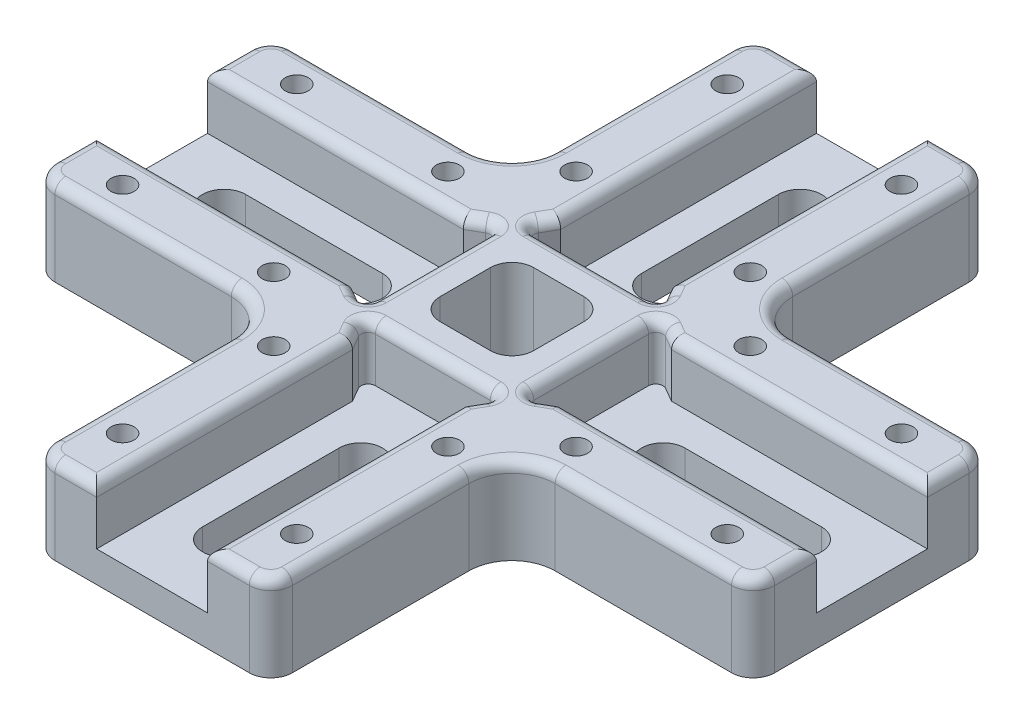
SolidWorks part; units mm, degrees
ref_plane "Front Plane" through (0, 0, 0) normal (0, 0, 1) x (1, 0, 0)
ref_plane "Top Plane" through (0, 0, 0) normal (0, 1, 0) x (1, 0, 0)
ref_plane "Right Plane" through (0, 0, 0) normal (1, 0, 0) x (0, 0, -1)
sketch "Sketch1" plane through (0, 0, 0) normal (0, 1, 0) x (1, 0, 0)
  line L0 (0, 54.7573) -> (0, -53.2039) construction
  line L1 (-56.4401, 0) -> (74.3042, 0) construction
  line L2 (0, 50) -> (-16.5, 50)
  line L3 (-16.5, 50) -> (-16.5, 16.5)
  line L4 (-16.5, 16.5) -> (-50, 16.5)
  line L5 (-50, 16.5) -> (-50, 0)
  line L6 (16.5, 50) -> (0, 50)
  line L7 (16.5, 16.5) -> (16.5, 50)
  line L8 (50, 16.5) -> (16.5, 16.5)
  line L9 (50, 0) -> (50, 16.5)
  line L10 (50, -16.5) -> (50, 0)
  line L11 (16.5, -16.5) -> (50, -16.5)
  line L12 (16.5, -50) -> (16.5, -16.5)
  line L13 (0, -50) -> (16.5, -50)
  line L14 (-16.5, -50) -> (0, -50)
  line L15 (-16.5, -16.5) -> (-16.5, -50)
  line L16 (-50, -16.5) -> (-16.5, -16.5)
  line L17 (-50, 0) -> (-50, -16.5)
  point P28 (0, 0)
  dimension "D1" = 50
  dimension "D2" = 50
  dimension "D3" = 16.5
  dimension "D4" = 16.5
  dimension "D5" = 4
extrude "Boss-Extrude1" add sketch "Sketch1" along normal blind 12
sketch "Sketch4" plane through (0, 12, 0) normal (0, 1, 0) x (1, 0, 0)
  line L0 (0, 50) -> (0, -50) construction
  line L1 (16.5, 50) -> (-16.5, 50) construction
  line L2 (-16.5, -50) -> (16.5, -50) construction
  line L3 (50, -7.7) -> (50, 7.7)
  line L4 (50, 7.7) -> (14.4641, 7.7)
  line L5 (14.4641, 7.7) -> (12.5, 8.834)
  line L6 (7.7, 50) -> (-7.7, 50)
  line L7 (-7.7, 50) -> (-7.7, 14.4641)
  line L8 (-7.7, 14.4641) -> (-8.834, 12.5)
  line L9 (-7.9679, 11) -> (7.9679, 11)
  line L10 (7.7, 14.4641) -> (8.834, 12.5)
  line L11 (7.7, 50) -> (7.7, 14.4641)
  line L14 (11, 7.9679) -> (11, -7.9679)
  line L15 (14.4641, -7.7) -> (12.5, -8.834)
  line L16 (50, -7.7) -> (14.4641, -7.7)
  line L17 (-7.7, -50) -> (7.7, -50)
  line L18 (7.7, -50) -> (7.7, -14.4641)
  line L19 (7.7, -14.4641) -> (8.834, -12.5)
  line L20 (7.9679, -11) -> (-7.9679, -11)
  line L21 (-7.7, -14.4641) -> (-8.834, -12.5)
  line L22 (-7.7, -50) -> (-7.7, -14.4641)
  line L23 (-50, 7.7) -> (-50, -7.7)
  line L24 (-50, -7.7) -> (-14.4641, -7.7)
  line L25 (-14.4641, -7.7) -> (-12.5, -8.834)
  line L26 (-11, -7.9679) -> (-11, 7.9679)
  line L27 (-14.4641, 7.7) -> (-12.5, 8.834)
  line L28 (-50, 7.7) -> (-14.4641, 7.7)
  arc A0 (-8.834, 12.5) -> (-7.9679, 11) centre (-7.9679, 12) ccw
  arc A1 (8.834, 12.5) -> (7.9679, 11) centre (7.9679, 12) cw
  arc A2 (12.5, 8.834) -> (11, 7.9679) centre (12, 7.9679) ccw
  arc A3 (12.5, -8.834) -> (11, -7.9679) centre (12, -7.9679) cw
  arc A4 (8.834, -12.5) -> (7.9679, -11) centre (7.9679, -12) ccw
  arc A5 (-8.834, -12.5) -> (-7.9679, -11) centre (-7.9679, -12) cw
  arc A6 (-12.5, -8.834) -> (-11, -7.9679) centre (-12, -7.9679) ccw
  arc A7 (-12.5, 8.834) -> (-11, 7.9679) centre (-12, 7.9679) cw
  point P6 (-4.9087, -5.1)
  point P18 (-9.7, 11)
  point P22 (0, 11)
  point P24 (9.7, 11)
  point P32 (11, 0)
  point P34 (11, -9.7)
  point P44 (0, -11)
  point P46 (-9.7, -11)
  point P56 (-11, 0)
  point P58 (-11, 9.7)
  point P59 (0, 0)
  dimension "D5" = 1
  dimension "D1" = 7.7
  dimension "D2" = 39
  dimension "D3" = 60
  dimension "D4" = 2
extrude "Cut-Extrude1" cut sketch "Sketch4" against normal blind 7.7
sketch "Sketch5" plane through (0, 12, 0) normal (0, 1, 0) x (1, 0, 0)
  line L0 (0, 0) -> (0, 61.5072) construction
  line L6 (-22.7133, 21) -> (27.3657, 21) construction
  line L7 (-24.8812, 42) -> (27.3657, 42) construction
  line L8 (-7.9679, 11) -> (7.9679, 11) construction
  line L9 (-7.7, 50) -> (-16.5, 50) construction
  line L10 (-12.1, 50) -> (-12.1, 12.9915) construction
  circle A0 centre (-12.1, 42) radius 1.6
  circle A1 centre (-12.1, 21) radius 1.6
  circle A2 centre (12.1, 21) radius 1.6
  circle A3 centre (12.1, 42) radius 1.6
  circle A4 centre (42, 12.1) radius 1.6
  circle A5 centre (21, 12.1) radius 1.6
  circle A6 centre (21, -12.1) radius 1.6
  circle A7 centre (42, -12.1) radius 1.6
  circle A8 centre (12.1, -42) radius 1.6
  circle A9 centre (12.1, -21) radius 1.6
  circle A10 centre (-12.1, -21) radius 1.6
  circle A11 centre (-12.1, -42) radius 1.6
  circle A12 centre (-42, -12.1) radius 1.6
  circle A13 centre (-21, -12.1) radius 1.6
  circle A14 centre (-21, 12.1) radius 1.6
  circle A15 centre (-42, 12.1) radius 1.6
  point P47 (0, 0)
  dimension "D3" = 3.2
  dimension "D4" = 3.2
  dimension "D1" = 10
  dimension "D2" = 8
extrude "Cut-Extrude2" cut sketch "Sketch5" against normal through all
sketch "Sketch7" plane through (0, 0, 0) normal (0, -1, 0) x (1, 0, 0)
  line L0 (0, 0) -> (0, 61.7218) construction
  circle A0 centre (-12.1, 42) radius 3.25
  circle A1 centre (-12.1, 21) radius 3.25
  circle A2 centre (12.1, 21) radius 3.25
  circle A3 centre (12.1, 42) radius 3.25
  circle A4 centre (42, 12.1) radius 3.25
  circle A5 centre (21, 12.1) radius 3.25
  circle A6 centre (21, -12.1) radius 3.25
  circle A7 centre (42, -12.1) radius 3.25
  circle A8 centre (12.1, -42) radius 3.25
  circle A9 centre (12.1, -21) radius 3.25
  circle A10 centre (-12.1, -21) radius 3.25
  circle A11 centre (-12.1, -42) radius 3.25
  circle A12 centre (-42, -12.1) radius 3.25
  circle A13 centre (-21, -12.1) radius 3.25
  circle A14 centre (-21, 12.1) radius 3.25
  circle A15 centre (-42, 12.1) radius 3.25
  point P39 (0, 0)
  dimension "D1" = 6.5
  dimension "D2" = 6.5
extrude "Cut-Extrude3" cut sketch "Sketch7" against normal blind 8.5
fillet "Fillet1" radius 6 4 edges at (-16.5, 6, -16.5) (16.5, 6, -16.5) (-16.5, 6, 16.5) (16.5, 6, 16.5)
fillet "Fillet3" radius 3 8 edges at (-50, 6, 16.5) (-50, 6, -16.5) (-16.5, 6, -50) (16.5, 6, -50) (50, 6, -16.5) (50, 6, 16.5) (16.5, 6, 50) (-16.5, 6, 50)
sketch "Sketch9" plane through (0, 12, 0) normal (0, 1, 0) x (1, 0, 0)
  line L0 (0, 0) -> (0, 50) construction
  line L1 (7.7, 50) -> (-7.7, 50) construction
  line L2 (0, 40) -> (0, 21) construction
  line L3 (3, 40) -> (3, 21)
  line L4 (-3, 40) -> (-3, 21)
  line L5 (-7.9679, 11) -> (7.9679, 11) construction
  line L6 (40, 0) -> (21, 0) construction
  line L7 (-3.5, 6.5) -> (3.5, 6.5)
  line L8 (-6.5, 3.5) -> (-6.5, -3.5)
  line L9 (-3.5, -6.5) -> (3.5, -6.5)
  line L10 (6.5, 3.5) -> (6.5, -3.5)
  line L11 (-6.5, 6.5) -> (6.5, -6.5) construction
  line L12 (-6.5, -6.5) -> (6.5, 6.5) construction
  line L13 (40, -3) -> (21, -3)
  line L14 (40, 3) -> (21, 3)
  line L15 (0, -40) -> (0, -21) construction
  line L16 (-3, -40) -> (-3, -21)
  line L17 (3, -40) -> (3, -21)
  line L18 (-40, 0) -> (-21, 0) construction
  line L19 (-40, 3) -> (-21, 3)
  line L20 (-40, -3) -> (-21, -3)
  arc A0 (3, 40) -> (-3, 40) centre (0, 40) ccw
  arc A1 (-3, 21) -> (3, 21) centre (0, 21) ccw
  arc A2 (3.5, 6.5) -> (6.5, 3.5) centre (3.5, 3.5) cw
  arc A3 (3.5, -6.5) -> (6.5, -3.5) centre (3.5, -3.5) ccw
  arc A4 (-6.5, -3.5) -> (-3.5, -6.5) centre (-3.5, -3.5) ccw
  arc A5 (-3.5, 6.5) -> (-6.5, 3.5) centre (-3.5, 3.5) ccw
  arc A6 (40, -3) -> (40, 3) centre (40, 0) ccw
  arc A7 (21, 3) -> (21, -3) centre (21, 0) ccw
  arc A8 (-3, -40) -> (3, -40) centre (0, -40) ccw
  arc A9 (3, -21) -> (-3, -21) centre (0, -21) ccw
  arc A10 (-40, 3) -> (-40, -3) centre (-40, 0) ccw
  arc A11 (-21, -3) -> (-21, 3) centre (-21, 0) ccw
  point P7 (0, 30.5)
  point P35 (30.5, 0)
  point P42 (0, -30.5)
  point P49 (-30.5, 0)
  point P54 (0, 0)
  dimension "D6" = 3
  dimension "D1" = 6
  dimension "D2" = 10
  dimension "D3" = 10
  dimension "D4" = 13
  dimension "D5" = 13
extrude "Cut-Extrude5" cut sketch "Sketch9" against normal through all
fillet "Fillet5" radius 1.5 56 edges at (-50, 12, -10.6) (-49.1213, 12, -15.6213) (-34.75, 12, -16.5) (-18.2574, 12, -18.2574) (-16.5, 12, -34.75) (-15.6213, 12, -49.1213) (8.267, 12, -13.4821) (8.834, 12, -11.5) (0, 12, -11) (-8.834, 12, -11.5) (10.6, 12, -50) (15.6213, 12, -49.1213) (16.5, 12, -34.75) (18.2574, 12, -18.2574) (34.75, 12, -16.5) (49.1213, 12, -15.6213) (13.4821, 12, -8.267) (11.5, 12, -8.834) (11, 12, 0) (11.5, 12, 8.834) (50, 12, 10.6) (49.1213, 12, 15.6213) (34.75, 12, 16.5) (18.2574, 12, 18.2574) (16.5, 12, 34.75) (15.6213, 12, 49.1213) (8.267, 12, 13.4821) (8.834, 12, 11.5) (0, 12, 11) (-8.834, 12, 11.5) (-10.6, 12, 50) (-15.6213, 12, 49.1213) (-16.5, 12, 34.75) (-18.2574, 12, 18.2574) (-34.75, 12, 16.5) (-49.1213, 12, 15.6213) (-13.4821, 12, 8.267) (-13.4821, 12, -8.267) (-11.5, 12, -8.834) (-11, 12, 0) (-10.6, 12, -50) (7.7, 12, -32.2321) (-8.267, 12, -13.4821) (-7.7, 12, -32.2321) (50, 12, -10.6) (32.2321, 12, -7.7) (13.4821, 12, 8.267) (32.2321, 12, 7.7) (10.6, 12, 50) (7.7, 12, 32.2321) (-8.267, 12, 13.4821) (-7.7, 12, 32.2321) (-50, 12, 10.6) (-32.2321, 12, -7.7) (-11.5, 12, 8.834) (-32.2321, 12, 7.7)
